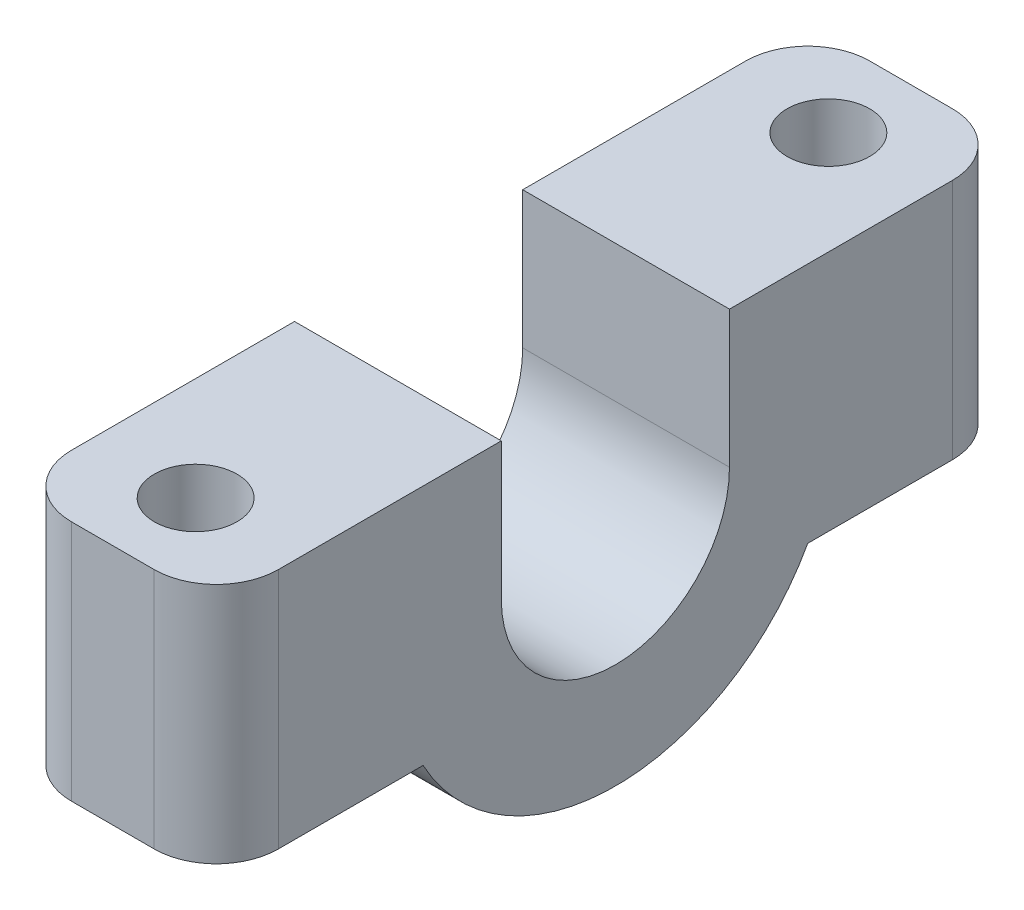
SolidWorks part; units mm, degrees
ref_plane "Front Plane" through (0, 0, 0) normal (0, 0, 1) x (1, 0, 0)
ref_plane "Top Plane" through (0, 0, 0) normal (0, 1, 0) x (1, 0, 0)
ref_plane "Right Plane" through (0, 0, 0) normal (1, 0, 0) x (0, 0, -1)
sketch "Sketch2" plane through (0, 0, 0) normal (1, 0, 0) x (0, 0, -1)
  line L0 (-10.035, 0) -> (10.035, 0) construction
  line L1 (-11.035, 0) -> (-38.6011, 0) construction
  line L2 (11.035, 0) -> (83.965, 0) construction
  line L3 (0, 0) -> (95, 0) construction
  line L4 (106.035, 0) -> (133.6011, 0) construction
  line L5 (-18.6011, -10.16) -> (-38.6011, -10.16)
  line L6 (18.6011, -10.16) -> (76.3989, -10.16) construction
  line L7 (113.6011, -10.16) -> (133.6011, -10.16) construction
  line L8 (-38.6011, 0) -> (-38.6011, -10.16)
  line L9 (133.6011, 0) -> (133.6011, -10.16) construction
  line L10 (-38.6011, 0) -> (-38.6011, 13.245)
  line L11 (-38.6011, 13.245) -> (-11.035, 13.245)
  line L12 (-11.035, 13.245) -> (-11.035, 0)
  line L13 (11.035, 0) -> (11.035, 13.245)
  line L14 (11.035, 13.245) -> (83.965, 13.245) construction
  line L15 (83.965, 13.245) -> (83.965, 0) construction
  line L16 (106.035, 0) -> (106.035, 13.245) construction
  line L17 (106.035, 13.245) -> (133.6011, 13.245) construction
  line L18 (133.6011, 13.245) -> (133.6011, 0) construction
  line L19 (11.035, 13.245) -> (38.6011, 13.245)
  line L20 (38.6011, 13.245) -> (38.6011, -10.16)
  line L21 (38.6011, -10.16) -> (18.6011, -10.16)
  arc A0 (-10.035, 0) -> (10.035, 0) centre (0, 0) ccw construction
  arc A1 (-11.035, 0) -> (11.035, 0) centre (0, 0) ccw
  arc A2 (84.965, 0) -> (105.035, 0) centre (95, 0) ccw construction
  arc A3 (83.965, 0) -> (106.035, 0) centre (95, 0) ccw construction
  arc A4 (-18.6011, -10.16) -> (18.6011, -10.16) centre (0, 0) ccw
  arc A5 (76.3989, -10.16) -> (113.6011, -10.16) centre (95, 0) ccw construction
  dimension "D6" = 10.16
  dimension "D1" = 20.07
  dimension "D3" = 95
  dimension "D5" = 20
  dimension "D7" = 10.16
  dimension "D8" = 10.16
  dimension "D9" = 13.245
  dimension "D2" = 1
  dimension "D4" = 1
extrude "Boss-Extrude1" add sketch "Sketch2" along normal blind 20
sketch "Sketch3" plane through (0, 13.245, 0) normal (0, 1, 0) x (1, 0, 0)
  line L0 (0, -38.6011) -> (0, -18.6011) construction
  line L1 (0, -38.6011) -> (0, -18.6011) construction
  line L2 (10, 0) -> (10, -30.6) construction
  line L3 (20, -38.6011) -> (0, -38.6011) construction
  line L4 (10, 0) -> (10, 30.6) construction
  line L5 (0, 0) -> (30.8763, 0) construction
  line L8 (20, -38.6011) -> (0, -38.6011) construction
  line L9 (20, -11.035) -> (20, -38.6011) construction
  circle A0 centre (10, -30.6) radius 4
  circle A2 centre (10, 30.6) radius 4
  point P14 (10, -38.6011)
  dimension "D1" = 8
  dimension "D2" = 61.2
extrude "Cut-Extrude1" cut sketch "Sketch3" against normal up to next
fillet "Fillet1" radius 6 4 edges at (0, 1.5425, 38.6011) (20, 1.5425, 38.6011) (20, 1.5425, -38.6011) (0, 1.5425, -38.6011)
